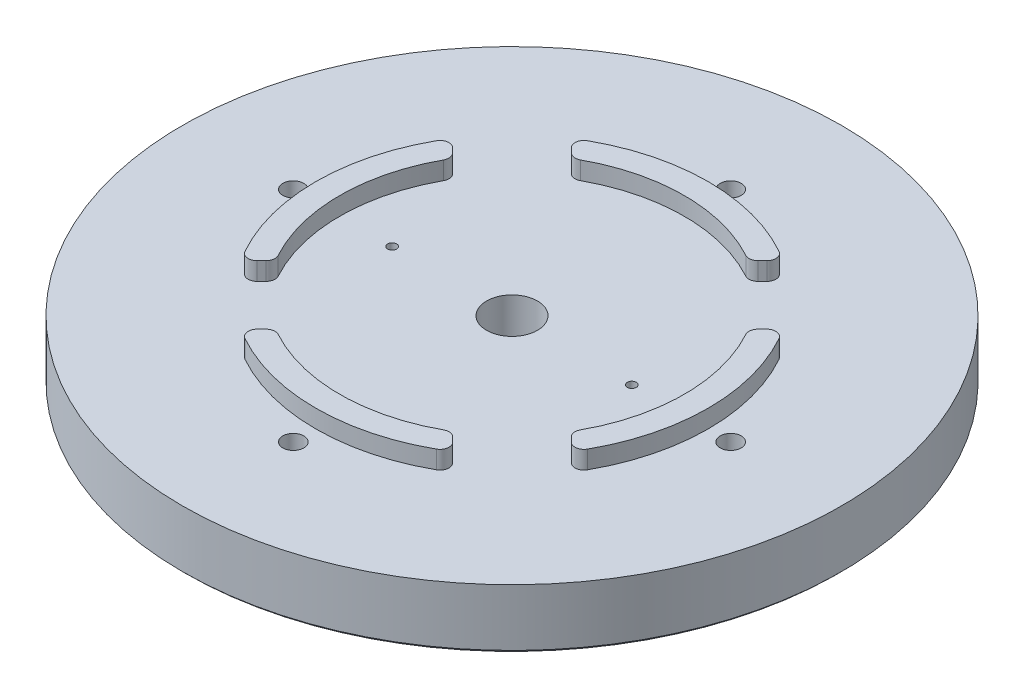
SolidWorks part; units mm, degrees
ref_plane "Front Plane" through (0, 0, 0) normal (0, 0, 1) x (1, 0, 0)
ref_plane "Top Plane" through (0, 0, 0) normal (0, 1, 0) x (1, 0, 0)
ref_plane "Right Plane" through (0, 0, 0) normal (1, 0, 0) x (0, 0, -1)
sketch "Sketch1" plane through (0, 0, 0) normal (0, 1, 0) x (1, 0, 0)
  circle A0 centre (0, 0) radius 55
  dimension "D1" = 110
extrude "Boss-Extrude1" add sketch "Sketch1" along normal blind 10
sketch "Sketch2" plane through (0, 10, 0) normal (0, 1, 0) x (1, 0, 0)
  circle A0 centre (0, 0) radius 4.25
  dimension "D1" = 8.5
extrude "Cut-Extrude1" cut sketch "Sketch2" against normal through all
sketch "Sketch3" plane through (0, 10, 0) normal (0, 1, 0) x (1, 0, 0)
  circle A0 centre (-20, 0) radius 0.75
  circle A1 centre (20, 0) radius 0.75
  dimension "D1" = 20
  dimension "D3" = 1.5
  dimension "D4" = 1.5
  dimension "D2" = 20
extrude "Cut-Extrude2" cut sketch "Sketch3" against normal through all
sketch "Sketch4" plane through (0, 10, 0) normal (0, 1, 0) x (1, 0, 0)
  circle A0 centre (0, 0) radius 28.75
  circle A1 centre (0, 0) radius 32.75
  dimension "D1" = 57.5
  dimension "D2" = 4
extrude "Boss-Extrude2" add sketch "Sketch4" along normal blind 3
sketch "Sketch5" plane through (0, 13, 0) normal (0, 1, 0) x (1, 0, 0)
  line L0 (-36.2036, 26.3041) -> (-26.3041, 36.2036)
  line L1 (-26.3041, 36.2036) -> (0, 9.8995)
  line L2 (0, 9.8995) -> (26.5276, 36.4271)
  line L3 (26.5276, 36.4271) -> (36.4271, 26.5276)
  line L4 (36.4271, 26.5276) -> (9.8995, 0)
  line L5 (9.8995, 0) -> (37.5634, -27.664)
  line L6 (37.5634, -27.664) -> (27.664, -37.5634)
  line L7 (27.664, -37.5634) -> (0, -9.8995)
  line L8 (0, -9.8995) -> (-22.8912, -32.7907)
  line L9 (-22.8912, -32.7907) -> (-32.7907, -22.8912)
  line L10 (-32.7907, -22.8912) -> (-9.8995, 0)
  line L11 (-9.8995, 0) -> (-36.2036, 26.3041)
  line L12 (20.2119, 20.2119) -> (10.4525, 10.4525) construction
  line L13 (-34.7142, 34.7142) -> (-18.412, 18.412) construction
  line L14 (0, 10.9849) -> (0, 32.5001) construction
  point P18 (-31.2539, 31.2539)
  point P20 (31.4773, 31.4773)
  point P21 (-27.841, -27.841)
  point P22 (32.6137, -32.6137)
  dimension "D1" = 45
  dimension "D2" = 45
  dimension "D3" = 14
  dimension "D4" = 14
  dimension "D5" = 14
  dimension "D6" = 14
extrude "Cut-Extrude3" cut sketch "Sketch5" against normal up to surface (3 mm away) up to face at (0, 10, 32.75)
fillet "Fillet1" radius 1.5 16 edges at (17.6728, 11.5, -27.5723) (-24.6673, 11.5, 14.7678) (-17.6728, 11.5, -27.5723) (-14.7678, 11.5, -24.6673) (14.7678, 11.5, -24.6673) (27.5723, 11.5, -17.6728) (24.6673, 11.5, -14.7678) (-27.5723, 11.5, -17.6728) (-24.6673, 11.5, -14.7678) (-27.5723, 11.5, 17.6728) (-14.7678, 11.5, 24.6673) (-17.6728, 11.5, 27.5723) (14.7678, 11.5, 24.6673) (17.6728, 11.5, 27.5723) (24.6673, 11.5, 14.7678) (27.5723, 11.5, 17.6728)
sketch "Sketch6" plane through (0, 10, 0) normal (0, 1, 0) x (1, 0, 0)
  line L0 (0, 0) -> (28.75, 0) construction
  line L1 (28.75, 0) -> (40.75, 0) construction
  circle A0 centre (36.5, 0) radius 1.75
  arc A1 (25.2226, -13.7979) -> (25.2226, 13.7979) centre (0, 0) ccw construction
  dimension "D1" = 3.5
  dimension "D2" = 12
  dimension "D3" = 36.5
extrude "Cut-Extrude4" cut sketch "Sketch6" against normal through all
sketch "Sketch7" plane through (0, 0, 0) normal (0, -1, 0) x (1, 0, 0)
  circle A0 centre (36.5, 0) radius 5.125
  dimension "D1" = 10.25
extrude "Cut-Extrude5" cut sketch "Sketch7" against normal blind 5
pattern_circular "CirPattern1" count 4 over 360 about axis through (0, 0, 0) along (0, 1, 0) of "Cut-Extrude4", "Cut-Extrude5"
chamfer "Chamfer1" distance 0.5 angle 45 1 edges at (0, 0, 55)
